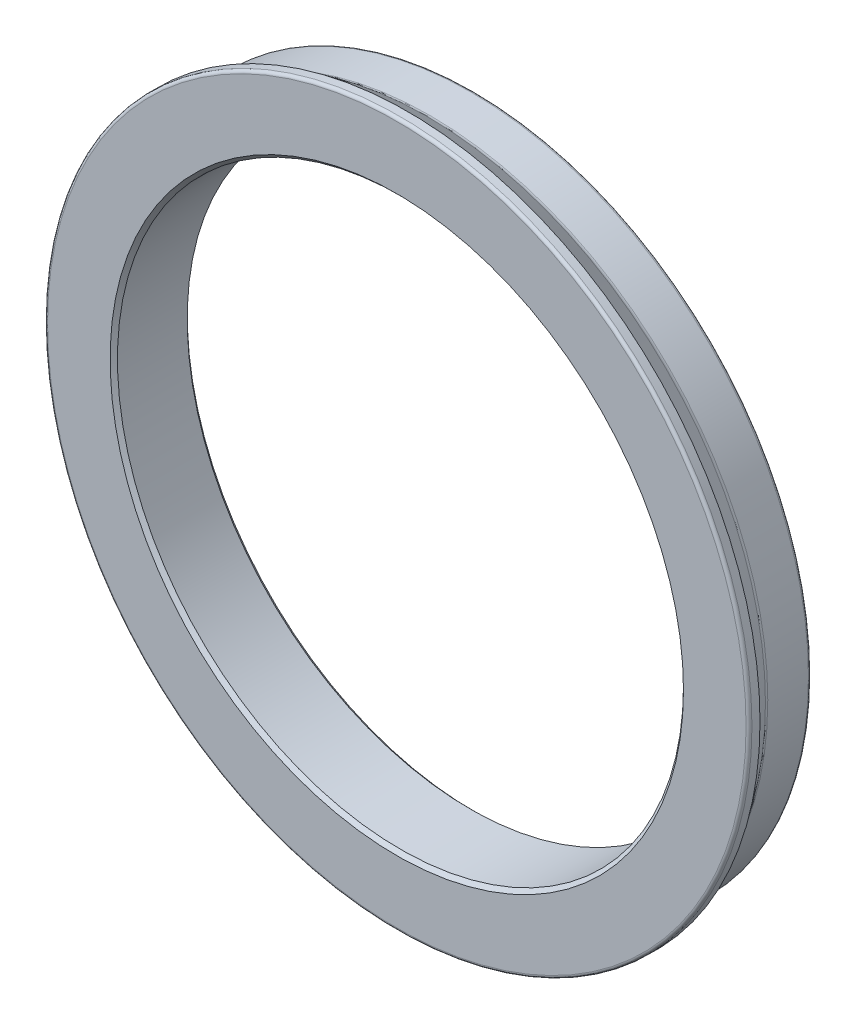
SolidWorks part; units mm, degrees
material "PETP Grey"
ref_plane "Front Plane" through (0, 0, 0) normal (0, 0, 1) x (1, 0, 0)
ref_plane "Top Plane" through (0, 0, 0) normal (0, 1, 0) x (1, 0, 0)
ref_plane "Right Plane" through (0, 0, 0) normal (1, 0, 0) x (0, 0, -1)
sketch "Sketch1" plane through (0, 0, 0) normal (1, 0, 0) x (0, 0, -1)
  line L0 (0, 0) -> (41.4438, 0) construction
  line L1 (0, 39.05) -> (0.5, 38.55)
  line L2 (0.4, 47.975) -> (1.5, 47.975)
  line L3 (0, 47.575) -> (0, 39.05)
  line L4 (0.5, 38.55) -> (10, 38.55)
  line L6 (10.5, 39.05) -> (10, 38.55)
  line L8 (1.5, 47.975) -> (4.0914, 46.124)
  line L9 (4.5564, 45.975) -> (10.1, 45.975)
  line L10 (10.5, 45.575) -> (10.5, 39.05)
  arc A0 (10.5, 45.575) -> (10.1, 45.975) centre (10.1, 45.575) ccw
  arc A1 (0, 47.575) -> (0.4, 47.975) centre (0.4, 47.575) cw
  arc A2 (4.0914, 46.124) -> (4.5564, 45.975) centre (4.5564, 46.775) ccw
  point P5 (0, 38.55)
  point P6 (5, 48.2)
  point P17 (10.5, 38.55)
  point P20 (4.3, 45.975)
  dimension "D7" = 6.2
  dimension "D8" = 0.4
  dimension "D9" = 0.4
  dimension "D10" = 0.8
  dimension "D1" = 77.1
  dimension "D2" = 95.95
  dimension "D3" = 1.5
  dimension "D4" = 91.95
  dimension "D5" = 10.5
revolve "Revolve1" add sketch "Sketch1" angle 360 about L0
